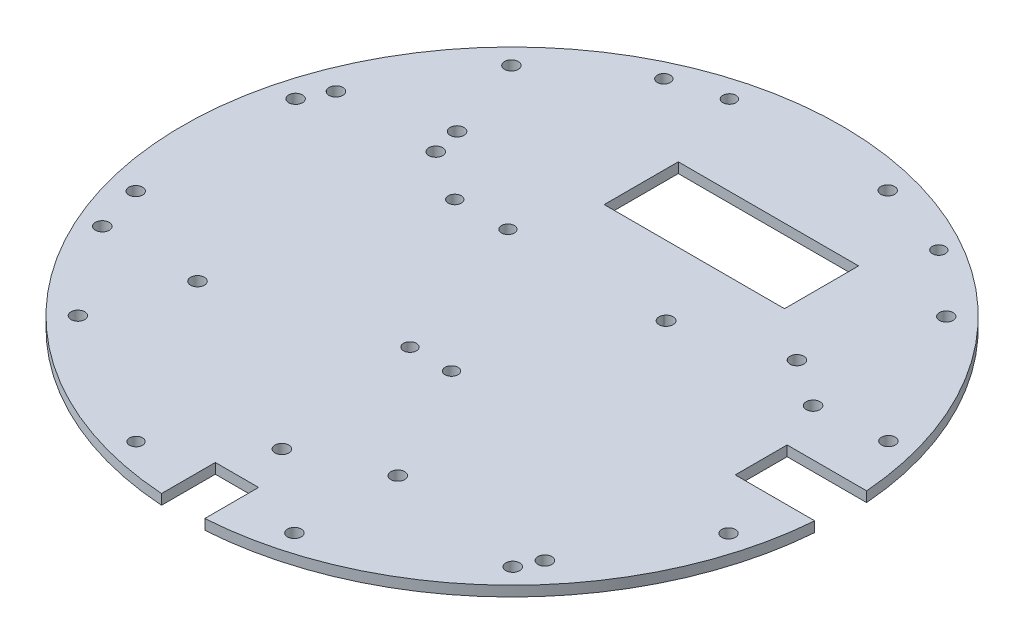
SolidWorks part; units mm, degrees
ref_plane "Front" through (0, 0, 0) normal (0, 0, 1) x (1, 0, 0)
ref_plane "Top" through (0, 0, 0) normal (0, 1, 0) x (1, 0, 0)
ref_plane "Right" through (0, 0, 0) normal (1, 0, 0) x (0, 0, -1)
sketch "Sketch1" plane through (0, 0, 0) normal (0, 1, 0) x (1, 0, 0)
  circle A1 centre (-41.7474, 24.1029) radius 1.6
  circle A2 centre (41.7474, 24.1029) radius 1.6
  circle A3 centre (0, 0) radius 76.2
  circle A4 centre (0, -53.2058) radius 1.6
  point P18 (0, 0)
  dimension "D1" = 152.4
extrude "Boss-Extrude1" add sketch "Sketch1" along normal blind 1 and the other way blind 1.3622
sketch "Sketch10" plane through (0, 1, 0) normal (0, 1, 0) x (1, 0, 0)
  line L0 (-5.6, -18) -> (4, -18) construction
  circle A0 centre (-5.6, -18) radius 1.5
  circle A5 centre (4, -18) radius 1.5
  dimension "D1" = 9.6
  dimension "D2" = 18
  dimension "D3" = 4
extrude "Cut-Extrude4" cut sketch "Sketch10" against normal through all
sketch "Sketch12" plane through (0, 1, 0) normal (0, 1, 0) x (1, 0, 0)
  line L0 (-65.34, 30.6187) -> (-65.34, -29.3813) construction
  line L1 (-60.672, 30.6187) -> (-60.672, 24.6187) construction
  line L2 (-60.8288, 24.6187) -> (-65.34, 24.6187) construction
  line L5 (-65.34, -29.3813) -> (-43.34, -29.3813) construction
  line L6 (-43.34, -29.3813) -> (-43.34, 30.6187) construction
  line L7 (-43.34, 30.6187) -> (-65.34, 30.6187) construction
  circle A0 centre (-65.34, 24.6187) radius 1.6
  circle A1 centre (-43.34, 30.6187) radius 1.6
  circle A2 centre (-65.34, -29.3813) radius 1.6
  circle A3 centre (-43.34, -29.3813) radius 1.6
  dimension "D1" = 60
  dimension "D2" = 22
extrude "Cut-Extrude6" cut sketch "Sketch12" against normal through all
sketch "Sketch13" plane through (0, 1, 0) normal (0, 1, 0) x (1, 0, 0)
  line L7 (18.7192, 16.8564) -> (52.7192, 16.8573) construction
  line L8 (52.7192, 16.8573) -> (52.721, -45.1427) construction
  line L9 (52.721, -45.1427) -> (18.721, -45.1436) construction
  line L10 (18.721, -45.1436) -> (18.7192, 16.8564) construction
  line L11 (18.7192, 16.8564) -> (52.7192, 16.8573) construction
  circle A0 centre (18.721, -45.1436) radius 1.6
  circle A1 centre (52.7192, 16.8573) radius 1.6
  circle A2 centre (52.721, -45.1427) radius 1.6
  circle A3 centre (18.7192, 16.8564) radius 1.6
  dimension "D1" = 34
  dimension "D2" = 62
  dimension "D3" = 45.1442
extrude "Cut-Extrude7" cut sketch "Sketch13" against normal blind 10
sketch "Sketch11" plane through (0, 1, 0) normal (0, 1, 0) x (1, 0, 0)
  line L0 (36.1033, 62.5531) -> (-29.9736, 65.0431) construction
  line L1 (-29.9736, 65.0431) -> (-29.9736, 16.7231) construction
  line L2 (-29.9736, 16.7231) -> (36.1033, 19.2131) construction
  line L3 (36.1033, 19.2131) -> (36.1033, 62.5531) construction
  circle A4 centre (36.1033, 62.5531) radius 1.5
  circle A5 centre (36.1033, 19.2131) radius 1.5 construction
  circle A6 centre (-29.9736, 65.0431) radius 1.5
  circle A7 centre (-29.9736, 16.7231) radius 1.5
  dimension "D1" = 66.0769
  dimension "D2" = 43.34
  dimension "D3" = 66.1238
  dimension "D4" = 66.1238
extrude "Cut-Extrude5" cut sketch "Sketch11" against normal blind 10
sketch "Sketch14" plane through (0, 1, 0) normal (0, 1, 0) x (1, 0, 0)
  line L0 (-5, -63.6027) -> (5, -63.6027)
  line L1 (5, -63.6027) -> (5, -77.6027)
  line L2 (5, -77.6027) -> (-5, -77.6027)
  line L3 (-5, -77.6027) -> (-5, -63.6027)
  line L5 (30, 32.9727) -> (-11.6792, 32.9727)
  line L6 (30, 32.9727) -> (30, 50.1004)
  line L7 (30, 50.1004) -> (-11.6792, 50.1004)
  line L8 (-11.6792, 32.9727) -> (-11.6792, 50.1004)
  line L12 (76.2, 0) -> (57.5816, 0) construction
  line L13 (57.5816, 6) -> (57.5816, -6)
  line L14 (57.5816, -6) -> (78.9976, -6)
  line L15 (78.9976, 6) -> (78.9976, -6)
  line L16 (78.9976, 0) -> (76.2, 0) construction
  line L18 (57.5816, 6) -> (78.9976, 6)
  circle A0 centre (0, -53.2058) radius 1.6 construction
  circle A1 centre (0, 0) radius 76.2 construction
  circle A2 centre (-50.2639, 50.1004) radius 1.5875
  circle A3 centre (-68.5201, 18.4796) radius 1.5875
  circle A4 centre (18.2562, -68.58) radius 1.5875
  circle A5 centre (-18.3448, -68.58) radius 1.499
  circle A6 centre (50.2639, 50.1004) radius 1.5875
  circle A7 centre (68.5201, 18.4796) radius 1.5875
  circle A8 centre (-17.8667, 16.9036) radius 1.499
  circle A9 centre (18.7344, 16.9036) radius 1.5875
  circle A11 centre (-18.3448, 68.58) radius 1.499
  circle A12 centre (18.2562, 68.58) radius 1.5875
  circle A13 centre (-50.2639, -50.1004) radius 1.5875
  circle A14 centre (-68.5201, -18.4796) radius 1.5875
  circle A15 centre (50.2639, -50.1004) radius 1.5875
  circle A16 centre (68.5201, -18.4796) radius 1.5875
  point P17 (0, 0)
  dimension "D2" = 5
  dimension "D1" = 10
  dimension "D3" = 14
  dimension "D5" = 12
  dimension "D6" = 6
extrude "Cut-Extrude8" cut sketch "Sketch14" against normal blind 10
